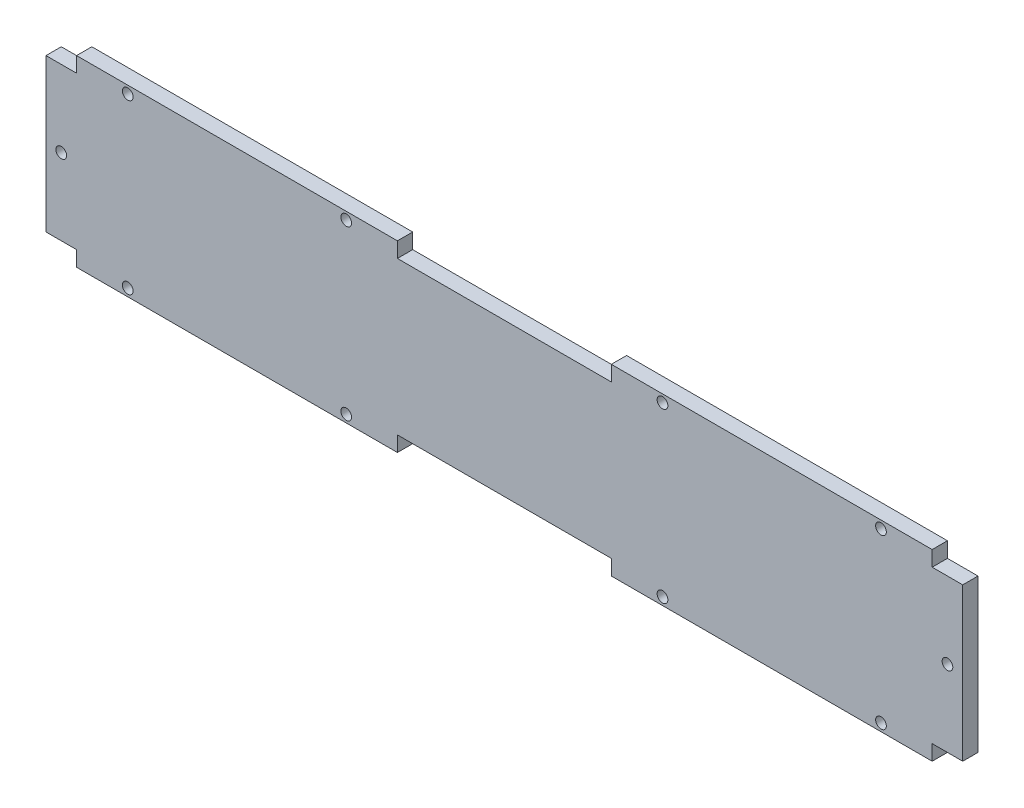
SolidWorks part; units mm, degrees
ref_plane "Front Plane" through (0, 0, 0) normal (0, 0, 1) x (1, 0, 0)
ref_plane "Top Plane" through (0, 0, 0) normal (0, 1, 0) x (1, 0, 0)
ref_plane "Right Plane" through (0, 0, 0) normal (1, 0, 0) x (0, 0, -1)
sketch "Sketch1" plane through (0, 0, 0) normal (0, 0, 1) x (1, 0, 0)
  line L0 (0, -1000) -> (0, 49000) construction
  line L1 (-140, -5) -> (-35, -5)
  line L2 (-140, -5) -> (-140, 0)
  line L3 (-140, 0) -> (-35, 0)
  line L4 (-35, -5) -> (-35, 0)
  line L5 (140, 0) -> (35, 0)
  line L6 (35, -5) -> (35, 0)
  line L7 (140, -5) -> (35, -5)
  line L8 (140, -5) -> (140, 0)
  line L9 (-1140, 25) -> (48860, 25) construction
  line L10 (-140, 0) -> (140, 0)
  line L11 (-140, 0) -> (-140, 50)
  line L12 (-140, 50) -> (140, 50)
  line L13 (140, 0) -> (140, 50)
  line L18 (140, 0) -> (150, 0)
  line L19 (140, 0) -> (140, 50)
  line L20 (140, 50) -> (140, -5)
  line L21 (140, 50) -> (150, 50)
  line L22 (-140, 0) -> (-150, 0)
  line L23 (-140, 0) -> (-140, 50)
  line L24 (-140, 50) -> (-150, 50)
  line L25 (-150, 0) -> (-150, 50)
  line L26 (150, 0) -> (150, 50)
  line L27 (140, 55) -> (140, 50)
  line L28 (140, 55) -> (35, 55)
  line L29 (35, 55) -> (35, 50)
  line L30 (140, 50) -> (35, 50)
  line L31 (-140, 50) -> (-35, 50)
  line L32 (-35, 55) -> (-35, 50)
  line L33 (-140, 55) -> (-35, 55)
  line L34 (-140, 55) -> (-140, 50)
  point P13 (0, 0)
  point P21 (-140, 25)
  dimension "D1" = 5
  dimension "D2" = 105
  dimension "D3" = 140
  dimension "D4" = 50
  dimension "D5" = 10
  dimension "D6" = 10
extrude "Boss-Extrude1" add sketch "Sketch1" along normal blind 5 contours L10 L0 L12 L11 L3 | L0 L10 L5 L13 L12 | L23 L22 L25 L24 | L19 L18 L26 L21 | L31 L32 L33 L34 | L30 L29 L28 L27
sketch "Sketch2" plane through (0, 0, 5) normal (0, 0, 1) x (1, 0, 0)
  line L0 (-87.5, -1005) -> (-87.5, 48995) construction
  line L1 (-140, -5) -> (-35, -5) construction
  line L3 (-35, -5) -> (-140, -5) construction
  line L4 (-35, -5) -> (-35, 0) construction
  line L5 (-35, 0) -> (-140, 0) construction
  line L6 (-140, -5) -> (-140, 0) construction
  line L7 (-140, -5) -> (-140, 0) construction
  line L8 (0, -1000) -> (0, 49000) construction
  line L9 (-140, -5) -> (-140, 0) construction
  line L10 (-1150, 25) -> (48850, 25) construction
  line L11 (-150, 0) -> (-150, 50) construction
  circle A0 centre (-123.25, -2.5) radius 1.75
  circle A1 centre (-51.75, -2.5) radius 1.75
  circle A2 centre (51.75, -2.5) radius 1.75
  circle A3 centre (123.25, -2.5) radius 1.75
  circle A4 centre (123.25, 52.5) radius 1.75
  circle A5 centre (51.75, 52.5) radius 1.75
  circle A6 centre (-51.75, 52.5) radius 1.75
  circle A7 centre (-123.25, 52.5) radius 1.75
  point P7 (-87.5, -5)
  point P17 (-140, -2.5)
  point P18 (-125, -2.5)
  point P33 (-150, 25)
  dimension "D1" = 3.5
  dimension "D2" = 15
extrude "Cut-Extrude1" cut sketch "Sketch2" against normal blind 5
sketch "Sketch3" plane through (0, 0, 5) normal (0, 0, 1) x (1, 0, 0)
  line L0 (-150, 0) -> (-150, 50) construction
  line L1 (0, -1000) -> (0, 49000) construction
  circle A0 centre (-145, 25) radius 1.75
  circle A1 centre (145, 25) radius 1.75
  point P5 (-150, 25)
  dimension "D1" = 3.5
  dimension "D2" = 5
extrude "Cut-Extrude2" cut sketch "Sketch3" against normal blind 10
